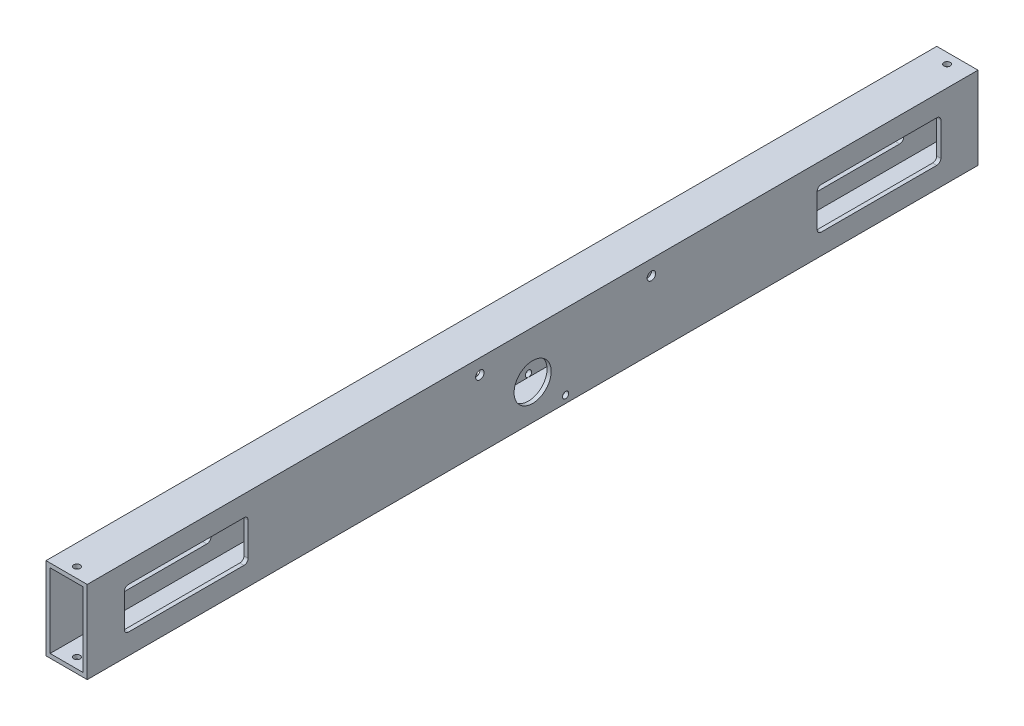
SolidWorks part; units mm, degrees
ref_plane "Front Plane" through (0, 0, 0) normal (0, 0, 1) x (1, 0, 0)
ref_plane "Top Plane" through (0, 0, 0) normal (0, 1, 0) x (1, 0, 0)
ref_plane "Right Plane" through (0, 0, 0) normal (1, 0, 0) x (0, 0, -1)
sketch "Sketch1" plane through (0, 0, 0) normal (0, 0, 1) x (1, 0, 0)
  line L1 (-12.1647, 2.5103) -> (19.5853, 2.5103)
  line L2 (-12.1647, 2.5103) -> (-12.1647, -60.9897)
  line L3 (-12.1647, -60.9897) -> (19.5853, -60.9897)
  line L4 (19.5853, 2.5103) -> (19.5853, -60.9897)
  line L5 (-8.9897, -0.6647) -> (16.4103, -0.6647)
  line L6 (-8.9897, -0.6647) -> (-8.9897, -57.8147)
  line L7 (-8.9897, -57.8147) -> (16.4103, -57.8147)
  line L8 (16.4103, -0.6647) -> (16.4103, -57.8147)
  dimension "D1" = 63.5
  dimension "D2" = 31.75
  dimension "D3" = 3.175
  dimension "D4" = 3.175
  dimension "D5" = 3.175
  dimension "D6" = 3.175
extrude "Boss-Extrude1" add sketch "Sketch1" along normal blind 685.8
sketch "Sketch3" plane through (-12.1647, 0, 0) normal (-1, 0, 0) x (0, 0, 1)
  line L0 (0, 2.5103) -> (0, -60.9897) construction
  line L1 (31.7754, -13.3647) -> (120.6754, -13.3647)
  line L2 (28.6004, -16.5397) -> (28.6004, -41.9397)
  line L3 (31.7754, -45.1147) -> (120.6754, -45.1147)
  line L4 (123.8504, -16.5397) -> (123.8504, -41.9397)
  line L5 (685.8, 2.5103) -> (0, 2.5103) construction
  line L6 (685.8, -60.9897) -> (0, -60.9897) construction
  line L7 (342.9, 2.5103) -> (342.9, -60.9897)
  line L8 (561.9496, -16.5397) -> (561.9496, -41.9397)
  line L9 (654.0246, -45.1147) -> (565.1246, -45.1147)
  line L10 (657.1996, -16.5397) -> (657.1996, -41.9397)
  line L11 (654.0246, -13.3647) -> (565.1246, -13.3647)
  arc A0 (28.6004, -41.9397) -> (31.7754, -45.1147) centre (31.7754, -41.9397) ccw
  arc A1 (120.6754, -45.1147) -> (123.8504, -41.9397) centre (120.6754, -41.9397) ccw
  arc A2 (120.6754, -13.3647) -> (123.8504, -16.5397) centre (120.6754, -16.5397) cw
  arc A3 (31.7754, -13.3647) -> (28.6004, -16.5397) centre (31.7754, -16.5397) ccw
  arc A4 (654.0246, -13.3647) -> (657.1996, -16.5397) centre (654.0246, -16.5397) cw
  arc A5 (565.1246, -13.3647) -> (561.9496, -16.5397) centre (565.1246, -16.5397) ccw
  arc A6 (565.1246, -45.1147) -> (561.9496, -41.9397) centre (565.1246, -41.9397) cw
  arc A7 (657.1996, -41.9397) -> (654.0246, -45.1147) centre (654.0246, -41.9397) cw
  dimension "D5" = 3.175
  dimension "D1" = 28.6004
  dimension "D2" = 15.875
  dimension "D3" = 15.875
  dimension "D4" = 95.25
extrude "Cut-Extrude1" cut sketch "Sketch3" against normal up to surface (31.75 mm away) contours L1 A3 L2 A0 L3 A1 L4 A2 | A7 L10 A4 L11 A5 L8 A6 L9 up to face at (19.5853, -29.2397, 342.9)
sketch "Sketch4" plane through (0, 2.5103, 0) normal (0, 1, 0) x (1, 0, 0)
  line L0 (19.5853, -685.8) -> (-12.1647, -685.8) construction
  line L1 (19.5853, 0) -> (-12.1647, 0) construction
  point P0 (3.7103, -677.8625)
  point P3 (3.7103, -685.8)
  point P4 (3.7103, -7.9375)
  dimension "D1" = 7.9375
  dimension "D2" = 7.9375
hole_wizard "#10 (0.1935) Diameter Hole1" positions "3DSketch1" profile "Sketch5" hole size "#10" standard "ANSI Inch" end condition through all
sketch3d "3DSketch1"
  point P0 (3.7103, 2.5103, 677.8625)
  point P3 (3.7103, 2.5103, 7.9375)
sketch "Sketch5" plane through (3.7103, 2.5103, 677.8625) normal (1, 0, 0) x (0, 0, 1)
  line L0 (0, 0) -> (0, 63.5)
  line L1 (0, 63.5) -> (2.4574, 63.5)
  line L2 (2.4574, 63.5) -> (2.4574, 0)
  line L5 (2.4574, 0) -> (0, 0)
  line L11 (0, -6.35) -> (0, 107.95) construction
  dimension "Thru Hole Dia." = 4.9149
  dimension "Thru Hole Depth" = 63.5
sketch "Sketch6" plane through (19.5853, 0, 0) normal (1, 0, 0) x (0, 0, -1)
  line L0 (-685.8, -60.9897) -> (0, -60.9897) construction
  line L4 (-685.8, -60.9897) -> (-685.8, 2.5103) construction
  circle A0 centre (-342.9, -34.0022) radius 14.2875
  circle A1 centre (-383.54, -8.9197) radius 3.2639
  circle A2 centre (-251.46, -8.9197) radius 3.2639
  circle A3 centre (-317.5, -55.4017) radius 2.413
  point P10 (-342.9, -60.9897)
  dimension "D1" = 28.575
  dimension "D4" = 6.5278
  dimension "D6" = 6.5278
  dimension "D8" = 4.826
  dimension "D2" = 26.9875
  dimension "D3" = 342.9
  dimension "D5" = 40.64
  dimension "D7" = 91.44
  dimension "D9" = 5.588
  dimension "D10" = 25.4
  dimension "D11" = 52.07
  dimension "D12" = 52.07
extrude "Cut-Extrude2" cut sketch "Sketch6" against normal up to surface (31.75 mm away)
